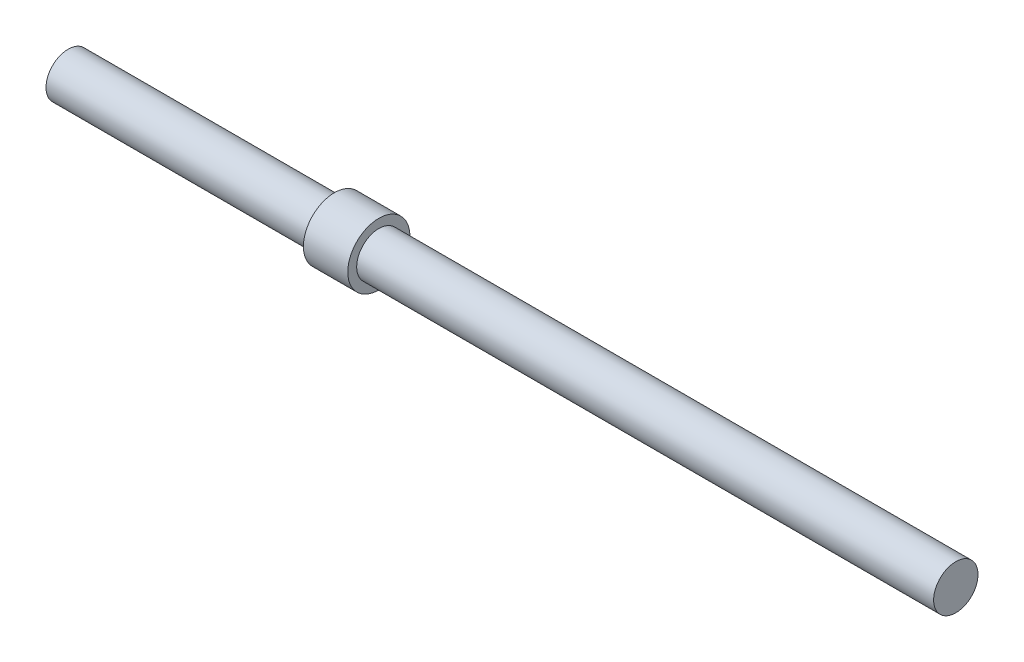
SolidWorks part; units mm, degrees
ref_plane "Front Plane" through (0, 0, 0) normal (0, 0, 1) x (1, 0, 0)
ref_plane "Top Plane" through (0, 0, 0) normal (0, 1, 0) x (1, 0, 0)
ref_plane "Right Plane" through (0, 0, 0) normal (1, 0, 0) x (0, 0, -1)
sketch "Sketch1" plane through (0, 0, 0) normal (1, 0, 0) x (0, 0, -1)
  circle A0 centre (0, 0) radius 5
  dimension "D1" = 10
extrude "Boss-Extrude1" add sketch "Sketch1" along normal mid plane 200
sketch "Sketch2" plane through (-100, 0, 0) normal (-1, 0, 0) x (0, 0, 1)
  circle A0 centre (0, 0) radius 7
  dimension "D1" = 14
extrude "Boss-Extrude2" add sketch "Sketch2" along normal blind 10 from offset 70
